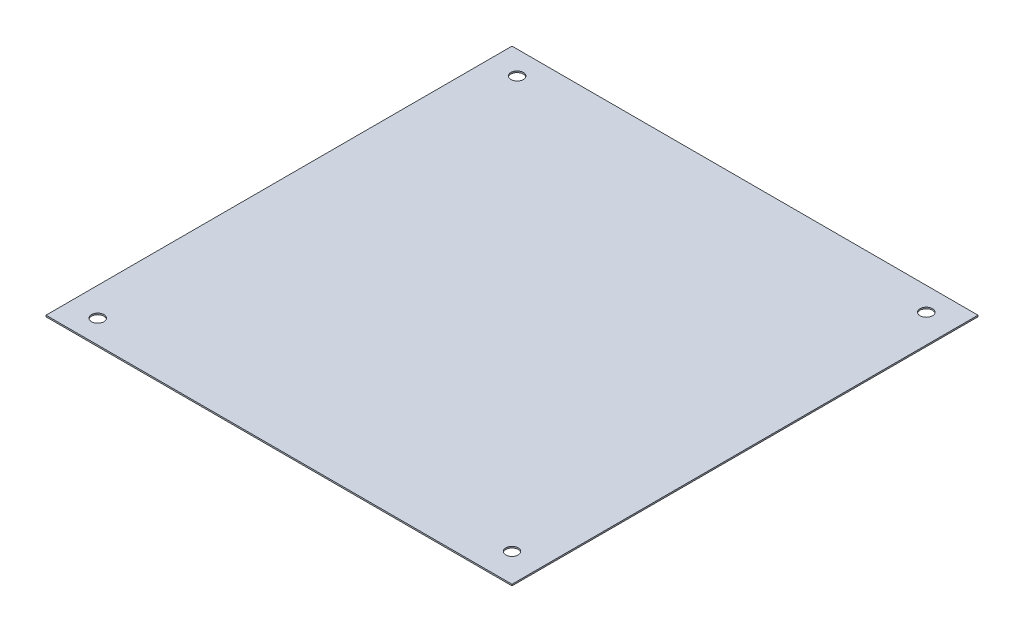
SolidWorks part; units mm, degrees
ref_plane "Front Plane" through (0, 0, 0) normal (0, 0, 1) x (1, 0, 0)
ref_plane "Top Plane" through (0, 0, 0) normal (0, 1, 0) x (1, 0, 0)
ref_plane "Right Plane" through (0, 0, 0) normal (1, 0, 0) x (0, 0, -1)
sketch "Sketch1" plane through (0, 0, 0) normal (0, 1, 0) x (1, 0, 0)
  line L1 (-127, -127) -> (127, -127)
  line L2 (-127, -127) -> (-127, 127)
  line L3 (-127, 127) -> (127, 127)
  line L4 (127, -127) -> (127, 127)
  line L5 (-127, -127) -> (127, 127) construction
  line L6 (-127, 127) -> (127, -127) construction
  line L7 (-111.506, -114.3) -> (111.506, -114.3) construction
  line L8 (-111.506, -114.3) -> (-111.506, 114.3) construction
  line L9 (-111.506, 114.3) -> (111.506, 114.3) construction
  line L10 (111.506, -114.3) -> (111.506, 114.3) construction
  line L11 (-111.506, -114.3) -> (111.506, 114.3) construction
  line L12 (-111.506, 114.3) -> (111.506, -114.3) construction
  circle A0 centre (-111.506, 114.3) radius 3.3782
  circle A1 centre (111.506, 114.3) radius 3.3782
  circle A2 centre (111.506, -111.506) radius 3.3782
  circle A3 centre (-111.506, -114.3) radius 3.3782
  point P0 (0, 0)
  point P6 (0, 0)
  dimension "D4" = 6.7564
  dimension "D1" = 254
  dimension "D2" = 228.6
  dimension "D3" = 223.012
extrude "Boss-Extrude1" add sketch "Sketch1" along normal blind 0.7937
